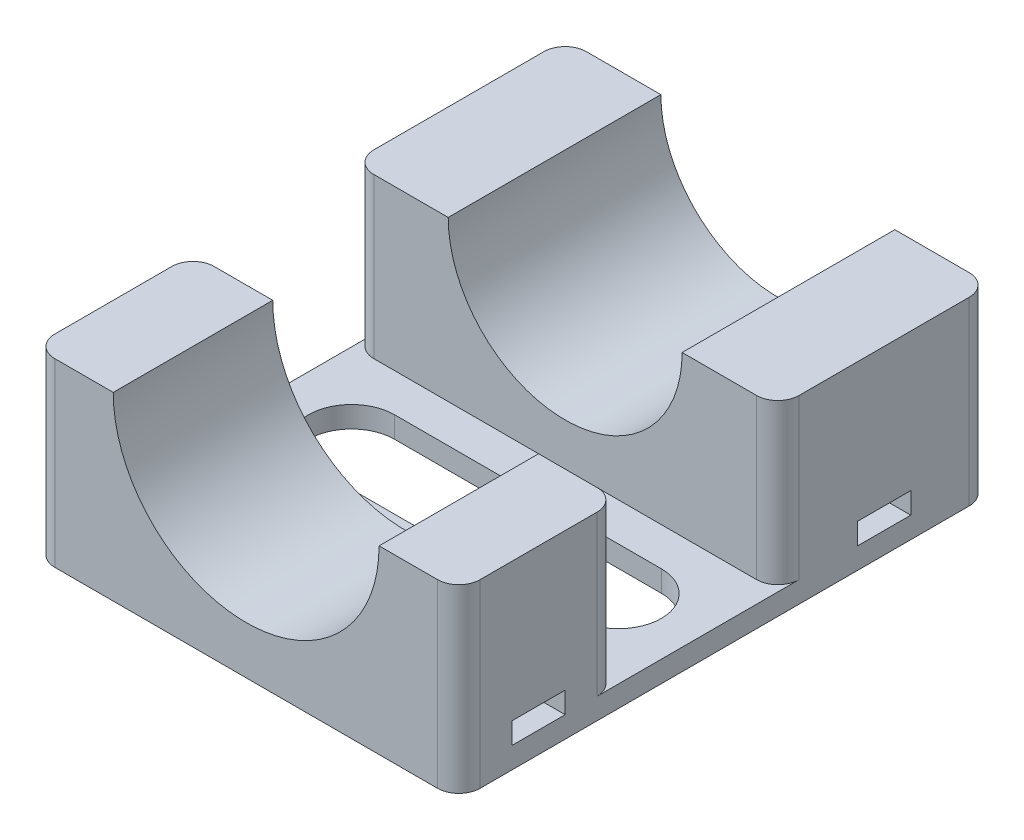
SolidWorks part; units mm, degrees
ref_plane "Plano frontal" through (0, 0, 0) normal (0, 0, 1) x (1, 0, 0)
ref_plane "Plano superior" through (0, 0, 0) normal (0, 1, 0) x (1, 0, 0)
ref_plane "Plano direito" through (0, 0, 0) normal (1, 0, 0) x (0, 0, -1)
sketch "Esboço1" plane through (0, 0, 0) normal (0, 1, 0) x (1, 0, 0)
  line L1 (-20, -25) -> (20, -25)
  line L2 (-20, -25) -> (-20, 25)
  line L3 (-20, 25) -> (20, 25)
  line L4 (20, -25) -> (20, 25)
  line L5 (-20, -25) -> (20, 25) construction
  line L6 (-20, 25) -> (20, -25) construction
  point P0 (0, 0)
  dimension "D1" = 40
  dimension "D2" = 50
extrude "Ressalto-extrusão1" add sketch "Esboço1" along normal blind 2 contours L3 L4 L1 L2
sketch "Esboço2" plane through (0, 2, 0) normal (0, 1, 0) x (1, 0, 0)
  line L0 (0, 34.9126) -> (0, -35.5556) construction
  line L1 (-20, 25) -> (20, 25)
  line L2 (-20, 25) -> (-20, 5)
  line L3 (-20, 5) -> (20, 5)
  line L4 (20, 25) -> (20, 5)
  line L5 (-20, 25) -> (20, 5) construction
  line L6 (-20, 5) -> (20, 25) construction
  line L7 (-20, -10) -> (20, -10)
  line L8 (-20, -10) -> (-20, -25)
  line L9 (-20, -25) -> (20, -25)
  line L10 (20, -10) -> (20, -25)
  line L11 (-20, -10) -> (20, -25) construction
  line L12 (-20, -25) -> (20, -10) construction
  line L13 (-20, 25) -> (20, 25) construction
  point P0 (0, 15)
  point P5 (0, -17.5)
  point P12 (0, 14.2094)
  point P13 (0, -20.7675)
  dimension "D1" = 15
  dimension "D2" = 20
  dimension "D3" = 40
  dimension "D4" = 40
  dimension "D5" = 50
  dimension "D6" = 0
extrude "Ressalto-extrusão2" add sketch "Esboço2" along normal blind 15
sketch "Esboço3" plane through (0, 0, 25) normal (0, 0, 1) x (1, 0, 0)
  line L0 (-20, 17) -> (20, 17) construction
  circle A0 centre (0, 17) radius 12.5
  dimension "D1" = 25
sketch "Esboço4" plane through (0, 0, -25) normal (0, 0, -1) x (-1, 0, 0)
  line L0 (-20, 17) -> (20, 17) construction
  circle A0 centre (0, 17) radius 11
  dimension "D1" = 22
extrude "Corte-extrusão1" cut sketch "Esboço3" against normal blind 22
extrude "Corte-extrusão2" cut sketch "Esboço4" against normal blind 22
sketch "Esboço5" plane through (0, 2, 0) normal (0, 1, 0) x (1, 0, 0)
  line L0 (-12.4492, -2.6417) -> (12.6331, -2.6417) construction
  line L1 (-12.4492, 1.4077) -> (12.6331, 1.4077)
  line L2 (-12.4492, -6.6912) -> (12.6331, -6.6912)
  arc A0 (-12.4492, 1.4077) -> (-12.4492, -6.6912) centre (-12.4492, -2.6417) ccw
  arc A1 (12.6331, -6.6912) -> (12.6331, 1.4077) centre (12.6331, -2.6417) ccw
  point P2 (0.092, -2.6417)
  point P7 (-12.4492, -2.5807)
  point P8 (0, 0)
  point P9 (12.6331, -2.6417)
extrude "Corte-extrusão3" cut sketch "Esboço5" against normal blind 22
sketch "Esboço6" plane through (-20, 0, 0) normal (-1, 0, 0) x (0, 0, 1)
  line L0 (-15, 17) -> (-15, 0) construction
  line L1 (-25, 17) -> (-5, 17) construction
  line L2 (25, 0) -> (-25, 0) construction
  line L3 (17.5, 17) -> (17.5, 0) construction
  line L4 (10, 17) -> (25, 17) construction
  line L6 (-17.5, 2) -> (-12.5, 2)
  line L7 (-17.5, 2) -> (-17.5, 4)
  line L8 (-17.5, 4) -> (-12.5, 4)
  line L9 (-12.5, 2) -> (-12.5, 4)
  line L10 (-17.5, 2) -> (-12.5, 4) construction
  line L11 (-17.5, 4) -> (-12.5, 2) construction
  line L12 (15, 2) -> (20, 2)
  line L13 (15, 2) -> (15, 4)
  line L14 (15, 4) -> (20, 4)
  line L15 (20, 2) -> (20, 4)
  line L16 (15, 2) -> (20, 4) construction
  line L17 (15, 4) -> (20, 2) construction
  point P10 (-15, 3)
  point P15 (17.5, 3)
  dimension "D1" = 5
  dimension "D2" = 2
  dimension "D3" = 2
  dimension "D4" = 2
  dimension "D5" = 5
  dimension "D6" = 2
extrude "Corte-extrusão4" cut sketch "Esboço6" against normal through all
fillet "Filete1" radius 2 1 edges at (-20, 9.5, 10)
fillet "Filete2" radius 2 1 edges at (-20, 9.5, -5)
fillet "Filete3" radius 2 1 edges at (-20, 8.5, 25)
fillet "Filete4" radius 2 1 edges at (-20, 8.5, -25)
fillet "Filete5" radius 2 1 edges at (20, 8.5, -25)
fillet "Filete6" radius 2 1 edges at (20, 9.5, 10)
fillet "Filete7" radius 2 1 edges at (20, 9.5, -5)
fillet "Filete8" radius 2 1 edges at (20, 8.5, 25)
